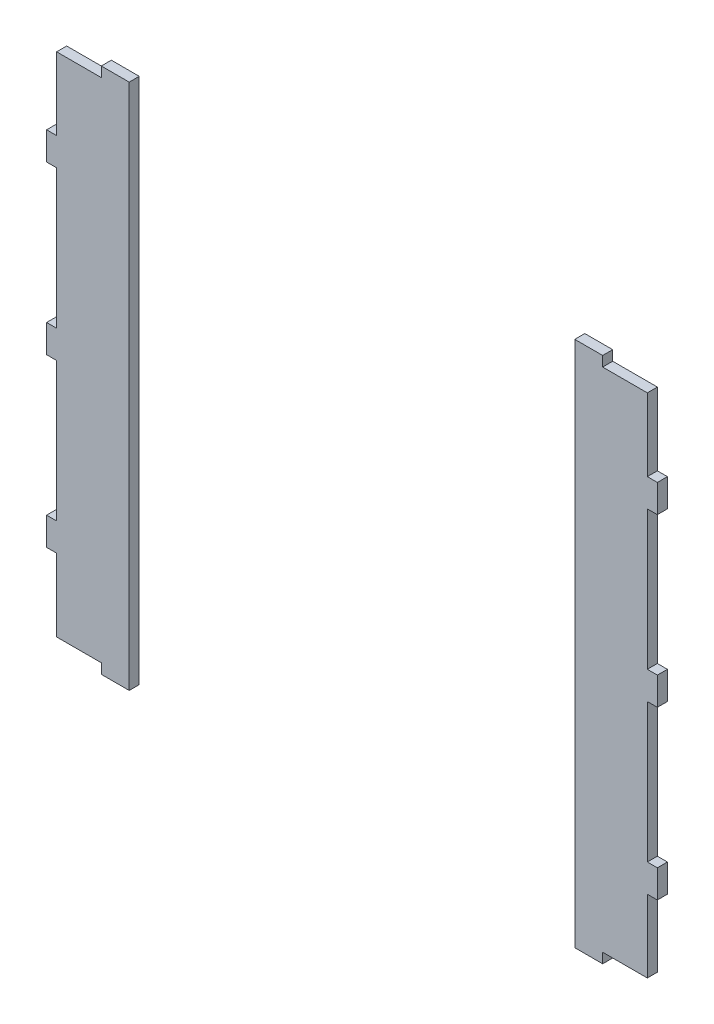
SolidWorks part; units mm, degrees
ref_plane "Front Plane" through (0, 0, 0) normal (0, 0, 1) x (1, 0, 0)
ref_plane "Top Plane" through (0, 0, 0) normal (0, 1, 0) x (1, 0, 0)
ref_plane "Right Plane" through (0, 0, 0) normal (1, 0, 0) x (0, 0, -1)
sketch "Sketch1" plane through (0, 0, 0) normal (0, 0, 1) x (1, 0, 0)
  line L0 (-961.2365, 328.9507) -> (-961.2365, 378.9507)
  line L8 (-943.2365, 807.9015) -> (-943.2365, 677.9015)
  line L9 (-943.2365, 677.9015) -> (-961.2365, 677.9015)
  line L10 (-961.2365, 627.9015) -> (-943.2365, 627.9015)
  line L11 (-943.2365, 627.9015) -> (-943.2365, 378.9507)
  line L12 (-943.2365, 378.9507) -> (-961.2365, 378.9507)
  line L13 (-961.2365, 627.9015) -> (-961.2365, 677.9015)
  line L18 (-414.1183, 825.9015) -> (-414.1183, 353.9507) construction
  line L19 (-961.2365, 353.9507) -> (-414.1183, 353.9507) construction
  line L20 (-943.2365, 807.9015) -> (-863.2365, 807.9015)
  line L21 (-863.2365, 807.9015) -> (-863.2365, 825.9015)
  line L22 (-863.2365, 825.9015) -> (-813.2365, 825.9015)
  line L23 (-813.2365, 825.9015) -> (-813.2365, 807.9015)
  line L24 (-813.2365, 807.9015) -> (-439.1183, 807.9015)
  line L25 (-439.1183, 807.9015) -> (-439.1183, 825.9015)
  line L26 (-843.2365, 603) -> (-843.2365, 0) construction
  line L28 (-439.1183, 825.9015) -> (-389.1183, 825.9015)
  line L29 (-788.166, 707.9015) -> (-779.041, 707.9015) construction
  line L30 (-439.1183, -118) -> (-389.1183, -118)
  line L31 (-439.1183, -100) -> (-439.1183, -118)
  line L32 (-813.2365, -100) -> (-439.1183, -100)
  line L33 (-813.2365, -118) -> (-813.2365, -100)
  line L34 (-863.2365, -118) -> (-813.2365, -118)
  line L35 (-863.2365, -100) -> (-863.2365, -118)
  line L36 (-943.2365, -100) -> (-863.2365, -100)
  line L37 (-961.2365, 80) -> (-961.2365, 30)
  line L38 (-943.2365, 328.9507) -> (-961.2365, 328.9507)
  line L39 (-943.2365, 80) -> (-943.2365, 328.9507)
  line L40 (-961.2365, 80) -> (-943.2365, 80)
  line L41 (-943.2365, 30) -> (-961.2365, 30)
  line L42 (-943.2365, -100) -> (-943.2365, 30)
  line L43 (-841.2365, 0) -> (-832.7445, 0) construction
  line L44 (115, -100) -> (115, 30)
  line L45 (115, 30) -> (133, 30)
  line L46 (133, 80) -> (115, 80)
  line L47 (115, 80) -> (115, 328.9507)
  line L48 (115, 328.9507) -> (133, 328.9507)
  line L49 (133, 80) -> (133, 30)
  line L50 (115, -100) -> (35, -100)
  line L51 (35, -100) -> (35, -118)
  line L52 (35, -118) -> (-15, -118)
  line L53 (-15, -118) -> (-15, -100)
  line L54 (-15, -100) -> (-389.1183, -100)
  line L55 (-389.1183, -100) -> (-389.1183, -118)
  line L56 (-389.1183, 807.9015) -> (-389.1183, 825.9015)
  line L57 (-15, 807.9015) -> (-389.1183, 807.9015)
  line L58 (-15, 825.9015) -> (-15, 807.9015)
  line L59 (35, 825.9015) -> (-15, 825.9015)
  line L60 (35, 807.9015) -> (35, 825.9015)
  line L61 (115, 807.9015) -> (35, 807.9015)
  line L62 (133, 627.9015) -> (133, 677.9015)
  line L63 (115, 378.9507) -> (133, 378.9507)
  line L64 (115, 627.9015) -> (115, 378.9507)
  line L65 (133, 627.9015) -> (115, 627.9015)
  line L66 (115, 677.9015) -> (133, 677.9015)
  line L67 (115, 807.9015) -> (115, 677.9015)
  line L68 (133, 328.9507) -> (133, 378.9507)
  line L69 (15, 603) -> (15, 0) construction
  point P24 (-961.2365, 353.9507)
  point P52 (-414.1183, -118)
  point P65 (133, 353.9507)
  dimension "D6" = 50
  dimension "D7" = 18
  dimension "D10" = 100
  dimension "D2" = 25
  dimension "D3" = 50
  dimension "D5" = 18
  dimension "D9" = 130
  dimension "D11" = 25
  dimension "D12" = 100
  dimension "D8" = 100
  dimension "D13" = 100
  dimension "D4" = 130
extrude "Boss-Extrude1" add sketch "Sketch1" along normal blind 18
sketch "Sketch2" plane through (0, 0, 0) normal (0, 0, -1) x (-1, 0, 0)
  line L0 (15, -118) -> (813.2365, -118)
  line L1 (813.2365, -118) -> (813.2365, 825.9015)
  line L2 (813.2365, 825.9015) -> (15, 825.9015)
  line L3 (15, 825.9015) -> (15, -118)
  line L4 (961.2365, 627.9015) -> (961.2365, 677.9015)
  line L5 (961.2365, 627.9015) -> (961.2365, 677.9015)
  line L6 (961.2365, 677.9015) -> (943.2365, 677.9015)
  line L7 (961.2365, 677.9015) -> (943.2365, 677.9015)
  line L64 (943.2365, 677.9015) -> (943.2365, 807.9015)
  line L65 (943.2365, 677.9015) -> (943.2365, 807.9015)
  line L66 (943.2365, 807.9015) -> (863.2365, 807.9015)
  line L67 (943.2365, 807.9015) -> (863.2365, 807.9015)
  line L68 (863.2365, 807.9015) -> (863.2365, 825.9015)
  line L69 (863.2365, 807.9015) -> (863.2365, 825.9015)
  line L70 (863.2365, 825.9015) -> (813.2365, 825.9015)
  line L71 (863.2365, 825.9015) -> (813.2365, 825.9015)
  line L72 (813.2365, 825.9015) -> (813.2365, 807.9015)
  line L73 (813.2365, 825.9015) -> (813.2365, 807.9015)
  line L74 (813.2365, 807.9015) -> (439.1183, 807.9015)
  line L75 (813.2365, 807.9015) -> (439.1183, 807.9015)
  line L76 (439.1183, 807.9015) -> (439.1183, 825.9015)
  line L77 (439.1183, 807.9015) -> (439.1183, 825.9015)
  line L78 (439.1183, 825.9015) -> (389.1183, 825.9015)
  line L79 (439.1183, 825.9015) -> (389.1183, 825.9015)
  line L80 (389.1183, 825.9015) -> (389.1183, 807.9015)
  line L81 (389.1183, 825.9015) -> (389.1183, 807.9015)
  line L82 (389.1183, 807.9015) -> (15, 807.9015)
  line L83 (389.1183, 807.9015) -> (15, 807.9015)
  line L84 (15, 807.9015) -> (15, 825.9015)
  line L85 (15, 807.9015) -> (15, 825.9015)
  line L86 (15, 825.9015) -> (-35, 825.9015)
  line L87 (15, 825.9015) -> (-35, 825.9015)
  line L88 (-35, 825.9015) -> (-35, 807.9015)
  line L89 (-35, 825.9015) -> (-35, 807.9015)
  line L90 (-35, 807.9015) -> (-115, 807.9015)
  line L91 (-35, 807.9015) -> (-115, 807.9015)
  line L92 (-115, 807.9015) -> (-115, 677.9015)
  line L93 (-115, 807.9015) -> (-115, 677.9015)
  line L94 (-115, 677.9015) -> (-133, 677.9015)
  line L95 (-115, 677.9015) -> (-133, 677.9015)
  line L96 (-133, 677.9015) -> (-133, 627.9015)
  line L97 (-133, 677.9015) -> (-133, 627.9015)
  line L98 (-133, 627.9015) -> (-115, 627.9015)
  line L99 (-133, 627.9015) -> (-115, 627.9015)
  line L100 (-115, 627.9015) -> (-115, 378.9507)
  line L101 (-115, 627.9015) -> (-115, 378.9507)
  line L102 (-115, 378.9507) -> (-133, 378.9507)
  line L103 (-115, 378.9507) -> (-133, 378.9507)
  line L104 (-133, 378.9507) -> (-133, 328.9507)
  line L105 (-133, 378.9507) -> (-133, 328.9507)
  line L106 (-133, 328.9507) -> (-115, 328.9507)
  line L107 (-133, 328.9507) -> (-115, 328.9507)
  line L108 (-115, 328.9507) -> (-115, 80)
  line L109 (-115, 328.9507) -> (-115, 80)
  line L110 (-115, 80) -> (-133, 80)
  line L111 (-115, 80) -> (-133, 80)
  line L112 (-133, 80) -> (-133, 30)
  line L113 (-133, 80) -> (-133, 30)
  line L114 (-133, 30) -> (-115, 30)
  line L115 (-133, 30) -> (-115, 30)
  line L116 (-115, 30) -> (-115, -100)
  line L117 (-115, 30) -> (-115, -100)
  line L118 (-115, -100) -> (-35, -100)
  line L119 (-115, -100) -> (-35, -100)
  line L120 (-35, -100) -> (-35, -118)
  line L121 (-35, -100) -> (-35, -118)
  line L122 (-35, -118) -> (15, -118)
  line L123 (-35, -118) -> (15, -118)
  line L124 (15, -118) -> (15, -100)
  line L125 (15, -118) -> (15, -100)
  line L126 (15, -100) -> (389.1183, -100)
  line L127 (15, -100) -> (389.1183, -100)
  line L128 (389.1183, -100) -> (389.1183, -118)
  line L129 (389.1183, -100) -> (389.1183, -118)
  line L130 (389.1183, -118) -> (439.1183, -118)
  line L131 (389.1183, -118) -> (439.1183, -118)
  line L132 (439.1183, -118) -> (439.1183, -100)
  line L133 (439.1183, -118) -> (439.1183, -100)
  line L134 (439.1183, -100) -> (813.2365, -100)
  line L135 (439.1183, -100) -> (813.2365, -100)
  line L136 (813.2365, -100) -> (813.2365, -118)
  line L137 (813.2365, -100) -> (813.2365, -118)
  line L138 (813.2365, -118) -> (863.2365, -118)
  line L139 (813.2365, -118) -> (863.2365, -118)
  line L140 (863.2365, -118) -> (863.2365, -100)
  line L141 (863.2365, -118) -> (863.2365, -100)
  line L142 (863.2365, -100) -> (943.2365, -100)
  line L143 (863.2365, -100) -> (943.2365, -100)
  line L144 (943.2365, -100) -> (943.2365, 30)
  line L145 (943.2365, -100) -> (943.2365, 30)
  line L146 (943.2365, 30) -> (961.2365, 30)
  line L147 (943.2365, 30) -> (961.2365, 30)
  line L148 (961.2365, 30) -> (961.2365, 80)
  line L149 (961.2365, 30) -> (961.2365, 80)
  line L150 (961.2365, 80) -> (943.2365, 80)
  line L151 (961.2365, 80) -> (943.2365, 80)
  line L152 (943.2365, 80) -> (943.2365, 328.9507)
  line L153 (943.2365, 80) -> (943.2365, 328.9507)
  line L154 (943.2365, 328.9507) -> (961.2365, 328.9507)
  line L155 (943.2365, 328.9507) -> (961.2365, 328.9507)
  line L156 (961.2365, 328.9507) -> (961.2365, 378.9507)
  line L157 (961.2365, 328.9507) -> (961.2365, 378.9507)
  line L158 (961.2365, 378.9507) -> (943.2365, 378.9507)
  line L159 (961.2365, 378.9507) -> (943.2365, 378.9507)
  line L160 (943.2365, 378.9507) -> (943.2365, 627.9015)
  line L161 (943.2365, 378.9507) -> (943.2365, 627.9015)
  line L162 (943.2365, 627.9015) -> (961.2365, 627.9015)
  line L163 (943.2365, 627.9015) -> (961.2365, 627.9015)
  dimension "D1" = 0
extrude "Cut-Extrude1" cut sketch "Sketch2" against normal through all contours L129 L127 L3 L0 | L135 L133 L0 L1 | L133 L135 L1 L2 L3 L127 L129 L0
sketch "Sketch3" plane through (0, 0, 0) normal (0, 0, -1) x (-1, 0, 0)
  line L0 (15, 603) -> (15, 0) construction
  line L1 (813.2365, 573) -> (15, 573)
  line L2 (813.2365, 573) -> (813.2365, 562.1515)
  line L3 (813.2365, 562.1515) -> (15, 562.1515)
  line L4 (15, 573) -> (15, 562.1515)
  line L5 (215.9071, 592.1515) -> (206.7821, 592.1515) construction
  dimension "D1" = 30
  dimension "D2" = 10.8485
extrude "Boss-Extrude2" [suppressed] add sketch "Sketch3" against normal up to surface (18 mm away)
equation "\"fingerlenght\"=50"
equation "\"D6@Sketch1\"=\"fingerlenght\""
equation "\"fingerendclearance\"=130"
equation "\"osbthickness\"=18"
equation "\"D7@Sketch1\"=\"osbthickness\""
equation "\"D2@Sketch1\"=\"fingerlenght\"/2"
equation "\"D3@Sketch1\"=\"fingerlenght\""
equation "\"D5@Sketch1\"=\"osbthickness\""
equation "\"D9@Sketch1\"=\"fingerendclearance\""
equation "\"D11@Sketch1\"=\"fingerlenght\"/2"
equation "\"wallclearance\"=100"
equation "\"D12@Sketch1\"=\"wallclearance\""
equation "\"D10@Sketch1\"=\"wallclearance\""
equation "\"D13@Sketch1\"=\"wallclearance\""
